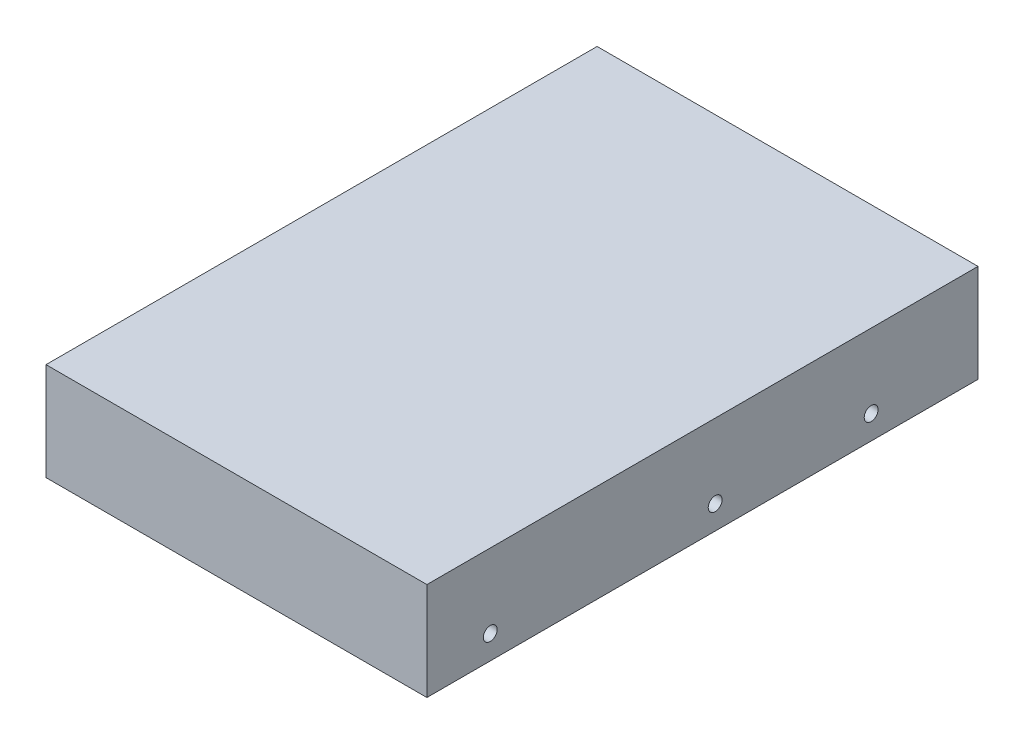
SolidWorks part; units mm, degrees
ref_plane "Спереди" through (0, 0, 0) normal (0, 0, 1) x (1, 0, 0)
ref_plane "Сверху" through (0, 0, 0) normal (0, 1, 0) x (1, 0, 0)
ref_plane "Справа" through (0, 0, 0) normal (1, 0, 0) x (0, 0, -1)
sketch "Эскиз1" plane through (0, 0, 0) normal (0, 1, 0) x (1, 0, 0)
  line L1 (0, 0) -> (101.6, 0)
  line L2 (0, 0) -> (0, 147)
  line L3 (0, 147) -> (101.6, 147)
  line L4 (101.6, 0) -> (101.6, 147)
  dimension "D1" = 147
  dimension "D2" = 101.6
extrude "Бобышка-Вытянуть1" add sketch "Эскиз1" along normal blind 26.1
sketch "Эскиз2" plane through (101.6, 0, 0) normal (1, 0, 0) x (0, 0, -1)
  line L0 (0, 6.35) -> (147, 6.35) construction
  line L1 (0, 26.1) -> (0, 0) construction
  line L2 (147, 26.1) -> (147, 0) construction
  line L3 (0, 0) -> (147, 0) construction
  point P8 (16.9, 6.35)
  point P9 (76.89, 6.35)
  point P10 (118.5, 6.35)
  dimension "D1" = 6.35
  dimension "D2" = 28.5
  dimension "D3" = 41.61
  dimension "D4" = 101.6
sketch "Эскиз3" plane through (0, 0, -147) normal (0, 0, -1) x (-1, 0, 0)
  text T0 "Разъемы"
hole_wizard "Сверло под метчик  спиральное M3.51" positions "Эскиз4" profile "Эскиз5" hole size "M3.5x0.6" standard "Ansi Metric"
sketch "Эскиз4" plane through (101.6, 0, 0) normal (1, 0, 0) x (0, 0, -1)
  point P0 (16.9, 6.35)
  point P3 (76.89, 6.35)
  point P6 (118.5, 6.35)
sketch "Эскиз5" plane through (101.6, 6.35, -16.9) normal (0, 1, 0) x (0, 0, -1)
  line L0 (0, 0) -> (0, 5.6116)
  line L1 (0, 5.6116) -> (1.85, 4.5)
  line L2 (1.85, 4.5) -> (1.85, 0)
  line L5 (1.85, 0) -> (0, 0)
  line L10 (0, 5.6116) -> (-1.85, 4.5) construction
  line L11 (0, -6.35) -> (0, 107.95) construction
  dimension "Диаметр отверстия" = 3.7
  dimension "Глубина отверстия" = 4.5
  dimension "Угол заточки сверла" = 118
ref_plane "Плоскость1" through (50.8, 0, 0) normal (-1, 0, 0) x (0, 0, 1)
mirror "Зеркальное отражение1" about plane through (50.8, 0, 0) normal (-1, 0, 0) of "Сверло под метчик  спиральное M3.51"
